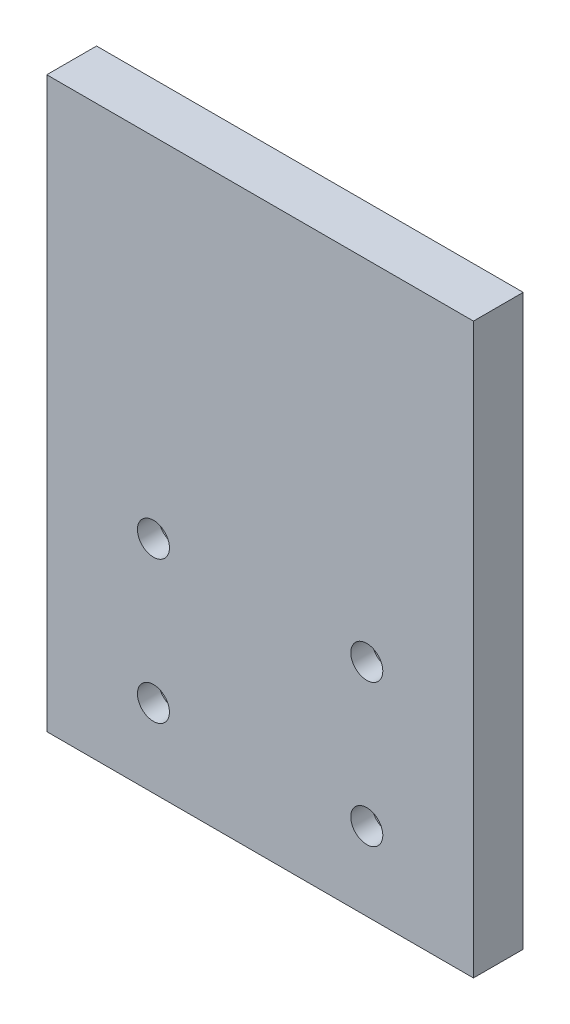
SolidWorks part; units mm, degrees
ref_plane "정면" through (0, 0, 0) normal (0, 0, 1) x (1, 0, 0)
ref_plane "윗면" through (0, 0, 0) normal (0, 1, 0) x (1, 0, 0)
ref_plane "우측면" through (0, 0, 0) normal (1, 0, 0) x (0, 0, -1)
sketch "스케치1" plane through (0, 0, 0) normal (0, 0, 1) x (1, 0, 0)
  line L1 (-30, 40) -> (30, 40)
  line L2 (-30, 40) -> (-30, -40)
  line L3 (-30, -40) -> (30, -40)
  line L4 (30, 40) -> (30, -40)
  line L5 (-30, 40) -> (30, -40) construction
  line L6 (-30, -40) -> (30, 40) construction
  point P0 (0, 0)
  dimension "D1" = 60
  dimension "D2" = 80
extrude "보스-돌출1" add sketch "스케치1" along normal blind 7
hole_wizard "M4 소켓 머리 캡 나사용 카운터보어1" positions "스케치4" profile "스케치3" counterbore size "M4" standard "KS" end condition through all
sketch "스케치4" plane through (0, 0, 0) normal (0, 0, -1) x (-1, 0, 0)
  line L0 (30, -40) -> (-30, -40) construction
  point P0 (-15, -29)
  point P2 (15, -29)
  point P4 (-15, -9)
  point P6 (15, -9)
  dimension "D1" = 11
  dimension "D2" = 11
  dimension "D3" = 15
  dimension "D4" = 15
  dimension "D5" = 15
  dimension "D6" = 15
  dimension "D7" = 20
  dimension "D8" = 20
sketch "스케치3" plane through (15, -29, 0) normal (1, 0, 0) x (0, 1, 0)
  line L0 (0, 0) -> (0, 7)
  line L1 (0, 7) -> (2.25, 7)
  line L3 (2.25, 7) -> (2.25, 4)
  line L4 (2.25, 4) -> (4, 4)
  line L5 (4, 4) -> (4, 0)
  line L7 (4, 0) -> (0, 0)
  line L11 (0, -6.35) -> (0, 107.95) construction
  dimension "관통 구멍 지름" = 4.5
  dimension "관통 구멍 깊이" = 7
  dimension "카운터보어 지름" = 8
  dimension "카운터보어 깊이" = 4
